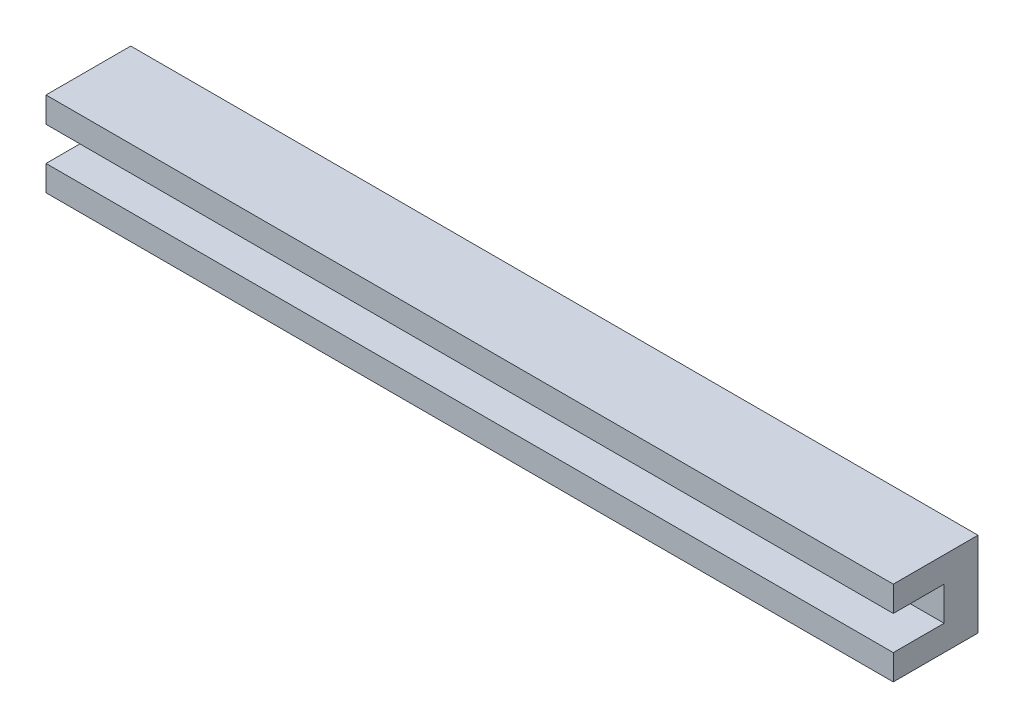
SolidWorks part; units mm, degrees
ref_plane "前视基准面" through (0, 0, 0) normal (0, 0, 1) x (1, 0, 0)
ref_plane "上视基准面" through (0, 0, 0) normal (0, 1, 0) x (1, 0, 0)
ref_plane "右视基准面" through (0, 0, 0) normal (1, 0, 0) x (0, 0, -1)
other "Configuration Table"
sketch "草图1" plane through (0, 0, 0) normal (0, 0, 1) x (1, 0, 0)
  line L1 (-48.9768, 20.9973) -> (51.0232, 20.9973)
  line L2 (-48.9768, 20.9973) -> (-48.9768, 10.9973)
  line L3 (-48.9768, 10.9973) -> (51.0232, 10.9973)
  line L4 (51.0232, 20.9973) -> (51.0232, 10.9973)
  dimension "D1" = 10
  dimension "D2" = 100
extrude "凸台-拉伸1" add sketch "草图1" along normal blind 4
sketch "草图2" plane through (0, 0, 4) normal (0, 0, 1) x (1, 0, 0)
  line L1 (-48.9768, 20.9973) -> (51.0232, 20.9973)
  line L2 (-48.9768, 20.9973) -> (-48.9768, 17.9973)
  line L3 (-48.9768, 17.9973) -> (51.0232, 17.9973)
  line L4 (51.0232, 20.9973) -> (51.0232, 17.9973)
  line L5 (51.0232, 10.9973) -> (51.0232, 20.9973) construction
  line L7 (-48.9768, 10.9973) -> (51.0232, 10.9973)
  line L8 (-48.9768, 10.9973) -> (-48.9768, 13.9973)
  line L9 (-48.9768, 13.9973) -> (51.0232, 13.9973)
  line L10 (51.0232, 10.9973) -> (51.0232, 13.9973)
  dimension "D1" = 3
  dimension "D2" = 100
  dimension "D3" = 3
  dimension "D4" = 100
extrude "凸台-拉伸2" add sketch "草图2" along normal blind 6
